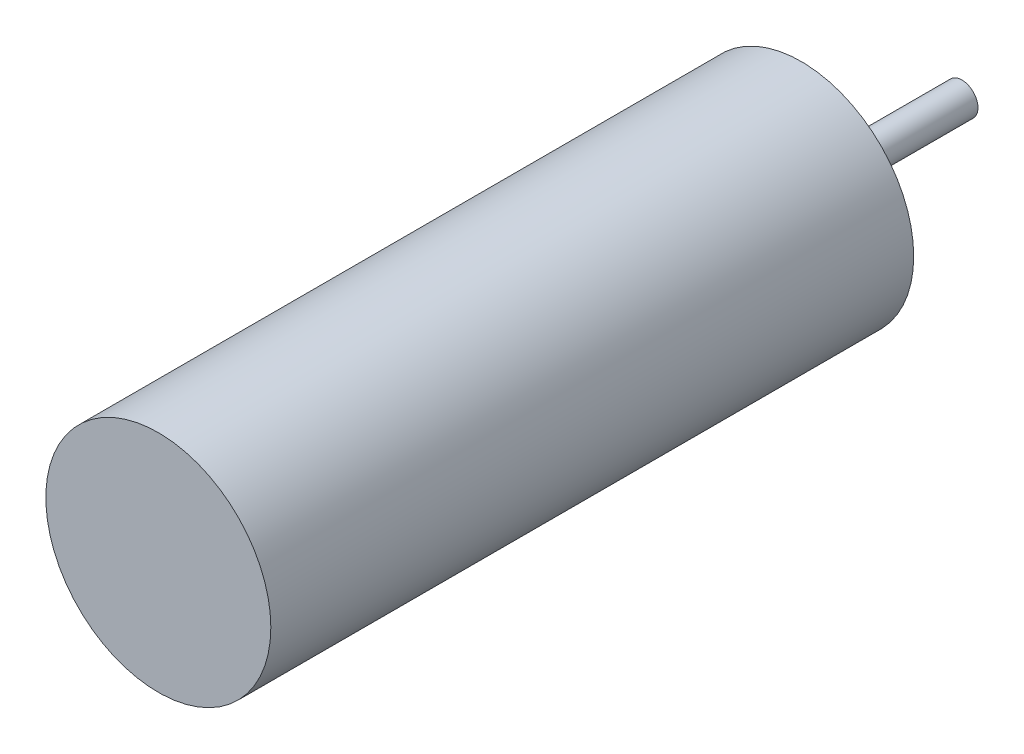
SolidWorks part; units mm, degrees
ref_plane "Plan de face" through (0, 0, 0) normal (0, 0, 1) x (1, 0, 0)
ref_plane "Plan de dessus" through (0, 0, 0) normal (0, 1, 0) x (1, 0, 0)
ref_plane "Plan de droite" through (0, 0, 0) normal (1, 0, 0) x (0, 0, -1)
sketch "Esquisse1" plane through (0, 0, 0) normal (0, 0, 1) x (1, 0, 0)
  circle A0 centre (0, 0) radius 3.5
  dimension "D1" = 7
extrude "Boss.-Extru.1" add sketch "Esquisse1" along normal blind 20
sketch "Esquisse2" plane through (0, 0, 0) normal (0, 0, -1) x (-1, 0, 0)
  circle A0 centre (0, 0) radius 0.5
  dimension "D1" = 1
extrude "Boss.-Extru.2" add sketch "Esquisse2" along normal blind 5
